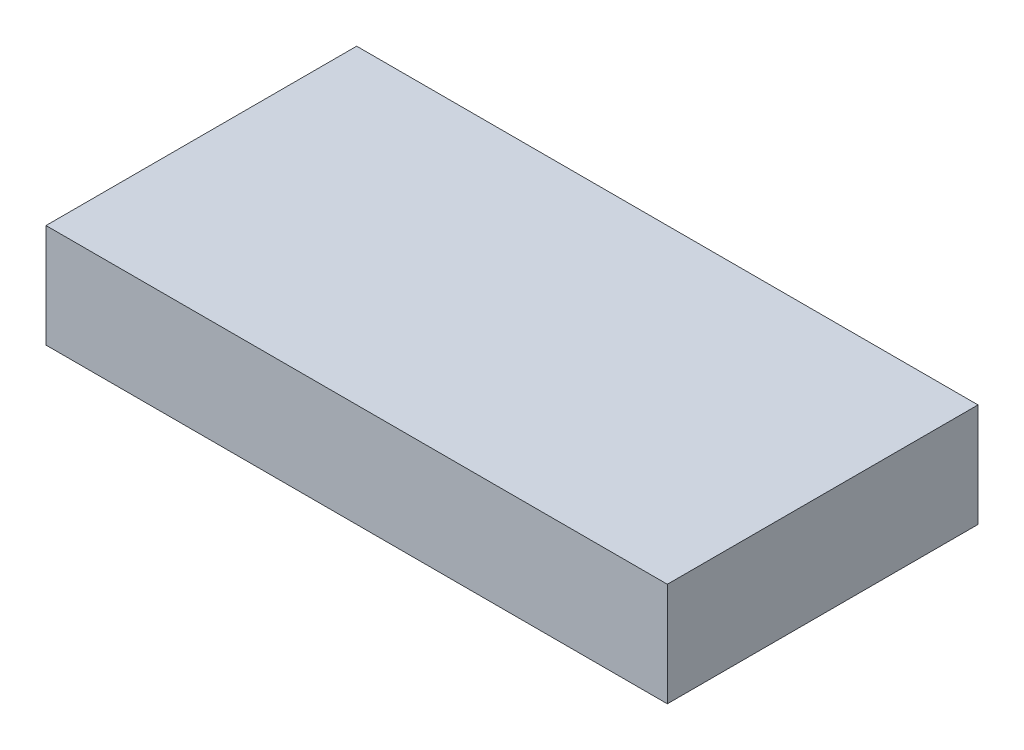
SolidWorks part; units mm, degrees
ref_plane "Front Plane" through (0, 0, 0) normal (0, 0, 1) x (1, 0, 0)
ref_plane "Top Plane" through (0, 0, 0) normal (0, 1, 0) x (1, 0, 0)
ref_plane "Right Plane" through (0, 0, 0) normal (1, 0, 0) x (0, 0, -1)
sketch "Sketch1" plane through (0, 0, 0) normal (0, 1, 0) x (1, 0, 0)
  line L0 (-152.4, 76.2) -> (152.4, -76.2) construction
  line L1 (-152.4, 76.2) -> (152.4, 76.2)
  line L2 (-152.4, 76.2) -> (-152.4, -76.2)
  line L3 (-152.4, -76.2) -> (152.4, -76.2)
  line L4 (152.4, 76.2) -> (152.4, -76.2)
  point P4 (0, 0)
  dimension "D1" = 304.8
  dimension "D2" = 152.4
extrude "Boss-Extrude1" add sketch "Sketch1" along normal blind 50.8
